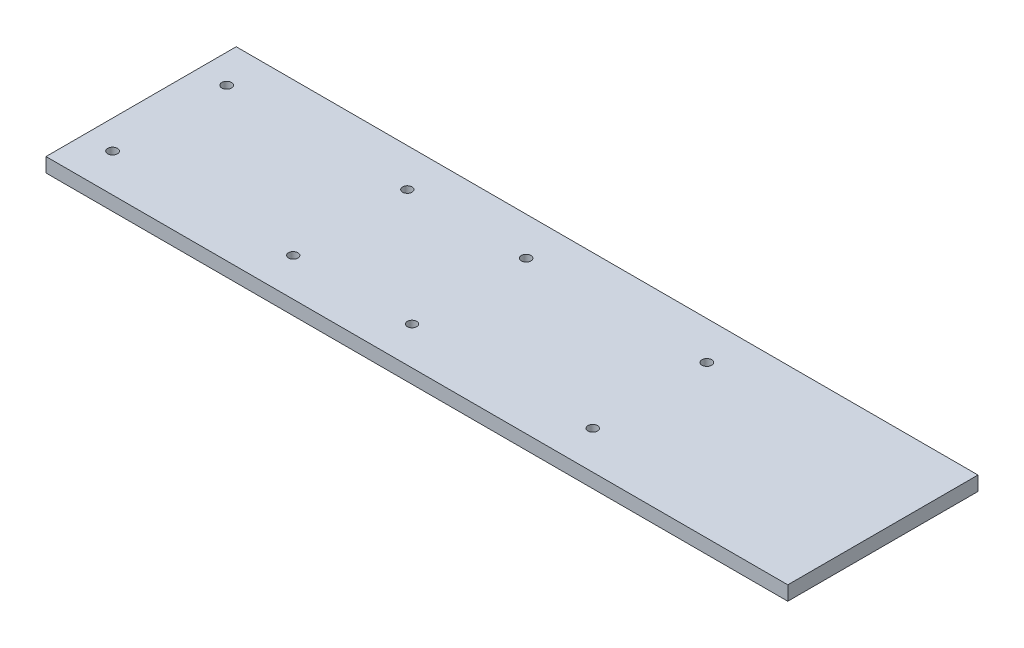
SolidWorks part; units mm, degrees
material "Pine"
ref_plane "Front Plane" through (0, 0, 0) normal (0, 0, 1) x (1, 0, 0)
ref_plane "Top Plane" through (0, 0, 0) normal (0, 1, 0) x (1, 0, 0)
ref_plane "Right Plane" through (0, 0, 0) normal (1, 0, 0) x (0, 0, -1)
sketch "Sketch1" plane through (0, 0, 0) normal (0, 1, 0) x (1, 0, 0)
  line L1 (0, 0) -> (990.6, 0)
  line L2 (0, 0) -> (0, -254)
  line L3 (0, -254) -> (990.6, -254)
  line L4 (990.6, 0) -> (990.6, -254)
  dimension "D1" = 254
  dimension "D2" = 990.6
extrude "Boss-Extrude1" add sketch "Sketch1" along normal blind 19.05
sketch "Sketch2" plane through (0, 19.05, 0) normal (0, 1, 0) x (1, 0, 0)
  circle A0 centre (38.1633, -203.2662) radius 6.4698
  circle A1 centre (38.1633, -50.9368) radius 6.4737
  circle A2 centre (279.4196, -203.2662) radius 6.2716
  circle A3 centre (279.4196, -50.9368) radius 6.2434
  circle A4 centre (438.1266, -50.9368) radius 6.3982
  circle A5 centre (438.1266, -203.2662) radius 6.2716
  circle A6 centre (679.3761, -203.2662) radius 6.3707
  circle A7 centre (679.3761, -50.9368) radius 6.4747
extrude "Cut-Extrude1" cut sketch "Sketch2" against normal blind 19.05
